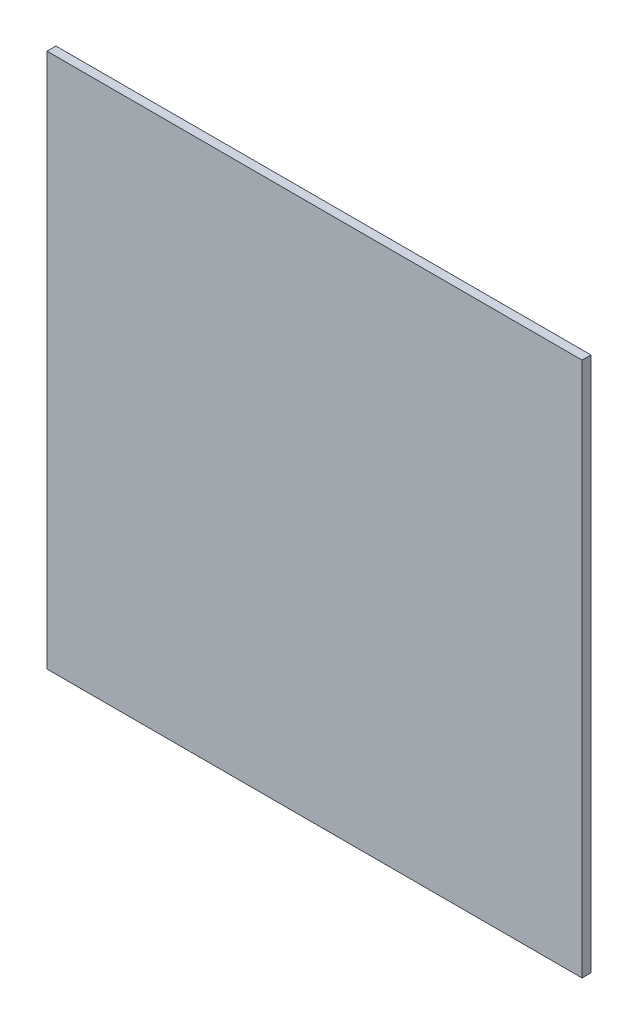
SolidWorks part; units mm, degrees
ref_plane "Front Plane" through (0, 0, 0) normal (0, 0, 1) x (1, 0, 0)
ref_plane "Top Plane" through (0, 0, 0) normal (0, 1, 0) x (1, 0, 0)
ref_plane "Right Plane" through (0, 0, 0) normal (1, 0, 0) x (0, 0, -1)
sketch "Sketch1" plane through (0, 0, 0) normal (0, 0, 1) x (1, 0, 0)
  line L0 (0, 180) -> (0, 0) construction
  line L1 (-180, 180) -> (180, 180)
  line L2 (-180, 180) -> (-180, -180)
  line L3 (-180, -180) -> (180, -180)
  line L4 (180, 180) -> (180, -180)
  line L5 (0, 0) -> (0, -180) construction
  dimension "D1" = 360
  dimension "D2" = 360
extrude "Boss-Extrude1" add sketch "Sketch1" along normal blind 6
sketch "Sketch2" plane through (0, 0, 0) normal (0, 0, 1) x (1, 0, 0)
  line L1 (100, -131) -> (-100, -131)
  line L2 (100, -131) -> (100, -150)
  line L3 (100, -150) -> (-100, -150)
  line L4 (-100, -131) -> (-100, -150)
  line L5 (0, 0) -> (0, -131) construction
  line L6 (-180, -180) -> (180, -180) construction
  dimension "D1" = 19
  dimension "D2" = 200
  dimension "D3" = 30
extrude "Boss-Extrude2" add sketch "Sketch2" against normal blind 70
sketch "Sketch3" plane through (100, 0, 0) normal (1, 0, 0) x (0, 0, -1)
  line L0 (0, -131) -> (0, 86.4679)
  line L1 (0, -180) -> (0, 180) construction
  line L2 (0, 86.4679) -> (70, -11)
  line L3 (70, -11) -> (70, -131)
  line L4 (70, -131) -> (0, -131)
  dimension "D1" = 120
  dimension "D2" = 120
extrude "Boss-Extrude3" add sketch "Sketch3" against normal blind 19
mirror "Mirror1" about plane through (0, 0, 0) normal (1, 0, 0) of "Boss-Extrude3"
